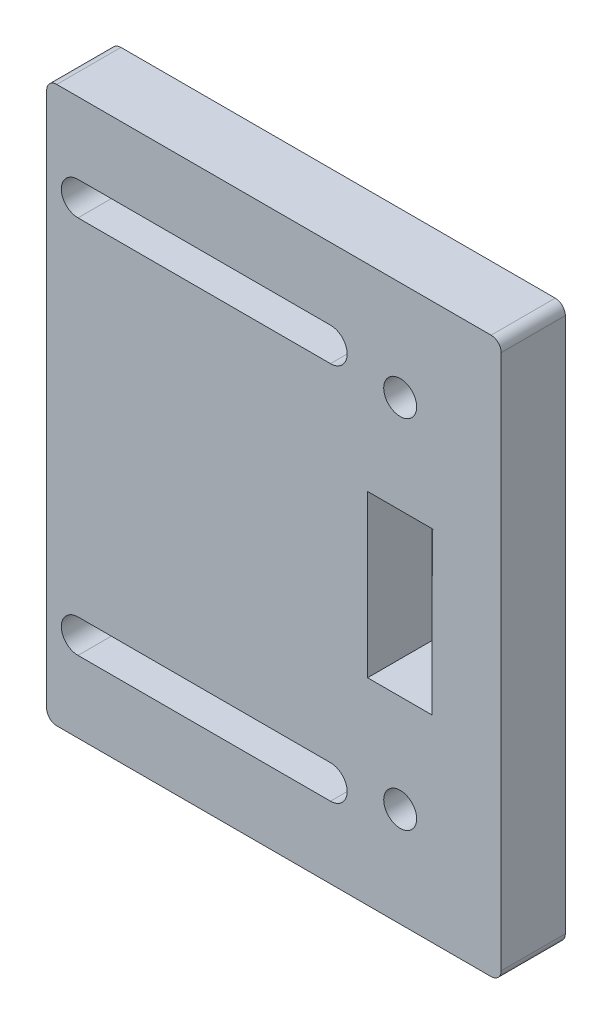
SolidWorks part; units mm, degrees
ref_plane "Front Plane" through (0, 0, 0) normal (0, 0, 1) x (1, 0, 0)
ref_plane "Top Plane" through (0, 0, 0) normal (0, 1, 0) x (1, 0, 0)
ref_plane "Right Plane" through (0, 0, 0) normal (1, 0, 0) x (0, 0, -1)
sketch "Sketch1" plane through (0, 0, 0) normal (0, 0, 1) x (1, 0, 0)
  line L0 (70, -110) -> (70, -90.31) construction
  line L1 (0, 0) -> (90, 0)
  line L2 (0, 0) -> (0, -110)
  line L3 (0, -110) -> (90, -110)
  line L4 (90, 0) -> (90, -110)
  line L6 (70, -39.0256) -> (76.45, -39.0256)
  line L8 (76.25, -70.9756) -> (70, -70.9756)
  line L9 (70, -70.9756) -> (63.55, -70.9756)
  line L10 (63.55, -70.9756) -> (63.55, -39.0256)
  line L11 (63.55, -39.0256) -> (70, -39.0256)
  line L12 (80, 0) -> (80, -19.69) construction
  line L14 (76.45, -39.0256) -> (76.25, -55)
  line L15 (76.25, -55) -> (76.25, -70.9756)
  dimension "D6" = 10
  dimension "D1" = 110
  dimension "D2" = 31.95
  dimension "D3" = 12.9
  dimension "D4" = 19.69
  dimension "D5" = 19.69
  dimension "D7" = 15.9744
  dimension "D8" = 80
extrude "Boss-Extrude2" add sketch "Sketch1" along normal blind 12.7
sketch "Sketch8" plane through (0, 0, 0) normal (0, 0, -1) x (-1, 0, 0)
  line L1 (-70, -110) -> (-70, -90.31) construction
  dimension "D1" = 19.69
  dimension "D2" = 20
hole_wizard "CSK for 1/4 Flat Head Machine Screw3" positions "Sketch9" profile "Sketch10" countersink size "1/4" standard "ANSI Inch" end condition through all
sketch "Sketch9" plane through (0, 0, 0) normal (0, 0, -1) x (-1, 0, 0)
  point P0 (-70, -90.31)
sketch "Sketch10" plane through (70, -90.31, 0) normal (1, 0, 0) x (0, 1, 0)
  line L0 (0, 0) -> (0, 12.7)
  line L1 (0, 12.7) -> (3.2639, 12.7)
  line L2 (3.2639, 12.7) -> (3.2639, 3.6524)
  line L3 (3.2639, 3.6524) -> (6.4389, 0)
  line L5 (6.4389, 0) -> (0, 0)
  line L6 (-3.2639, 3.6524) -> (-6.4389, 0) construction
  line L11 (0, -6.35) -> (0, 107.95) construction
  dimension "Thru Hole Dia." = 6.5278
  dimension "Thru Hole Depth" = 12.7
  dimension "Near C'Sink Dia." = 12.8778
  dimension "Near C'Sink Angle" = 82
sketch "Sketch11" plane through (0, 0, 0) normal (0, 0, -1) x (-1, 0, 0)
  line L0 (-70, 0) -> (-70, -19.69)
  dimension "D1" = 19.69
  dimension "D2" = 20
hole_wizard "CSK for 1/4 Flat Head Machine Screw4" positions "Sketch12" profile "Sketch13" countersink size "1/4" standard "ANSI Inch" end condition through all
sketch "Sketch12" plane through (0, 0, 0) normal (0, 0, -1) x (-1, 0, 0)
  point P0 (-70, -19.69)
sketch "Sketch13" plane through (70, -19.69, 0) normal (1, 0, 0) x (0, 1, 0)
  line L0 (0, 0) -> (0, 12.7)
  line L1 (0, 12.7) -> (3.2639, 12.7)
  line L2 (3.2639, 12.7) -> (3.2639, 3.6524)
  line L3 (3.2639, 3.6524) -> (6.4389, 0)
  line L5 (6.4389, 0) -> (0, 0)
  line L6 (-3.2639, 3.6524) -> (-6.4389, 0) construction
  line L11 (0, -6.35) -> (0, 107.95) construction
  dimension "Thru Hole Dia." = 6.5278
  dimension "Thru Hole Depth" = 12.7
  dimension "Near C'Sink Dia." = 12.8778
  dimension "Near C'Sink Angle" = 82
fillet "Fillet1" radius 2 4 edges at (0, 0, 6.35) (90, 0, 6.35) (0, -110, 6.35) (90, -110, 6.35)
sketch "Sketch15" plane through (0, 0, 0) normal (0, 0, -1) x (-1, 0, 0)
  line L0 (-56.2003, -14.185) -> (-6.2003, -14.185)
  line L1 (-56.2003, -20.785) -> (-6.2003, -20.785)
  line L2 (0, -55) -> (-82.6046, -55) construction
  line L3 (0, -2) -> (0, -108) construction
  line L4 (-56.2003, -89.215) -> (-6.2003, -89.215)
  line L5 (-56.2003, -95.815) -> (-6.2003, -95.815)
  arc A0 (-6.2003, -14.185) -> (-6.2003, -20.785) centre (-6.2003, -17.485) cw
  arc A1 (-56.2003, -20.785) -> (-56.2003, -14.185) centre (-56.2003, -17.485) cw
  arc A2 (-6.2003, -95.815) -> (-6.2003, -89.215) centre (-6.2003, -92.515) ccw
  arc A3 (-56.2003, -89.215) -> (-56.2003, -95.815) centre (-56.2003, -92.515) ccw
  dimension "D3" = 3.3
  dimension "D4" = 68.43
  dimension "D1" = 50
  dimension "D2" = 50
extrude "Cut-Extrude1" cut sketch "Sketch15" against normal through all
